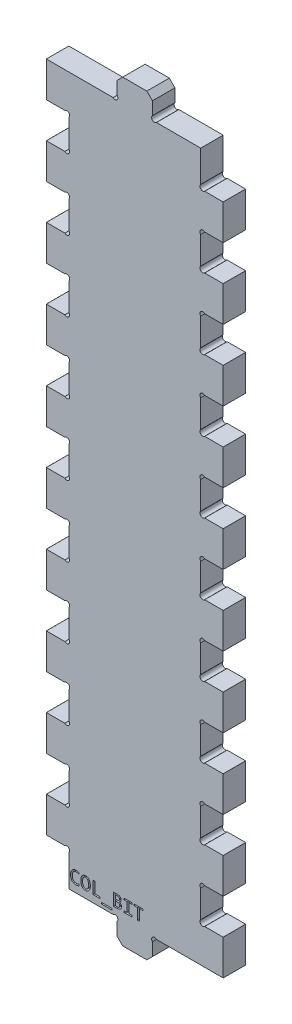
SolidWorks part; units mm, degrees
material "PVC Rigid"
ref_plane "Front Plane" through (0, 0, 0) normal (0, 0, 1) x (1, 0, 0)
ref_plane "Top Plane" through (0, 0, 0) normal (0, 1, 0) x (1, 0, 0)
ref_plane "Right Plane" through (0, 0, 0) normal (1, 0, 0) x (0, 0, -1)
sketch "Model" [suppressed]
  dimension "D3" = 0.7937
  dimension "D1" = 10
  dimension "D2" = 10
sketch "Sketch1" plane through (0, 0, 0) normal (0, 0, 1) x (1, 0, 0)
  line L1 (0, 0) -> (50, 0)
  line L2 (0, 0) -> (0, 200.0001)
  line L3 (0, 200.0001) -> (50, 200.0001)
  line L4 (50, 0) -> (50, 200.0001)
  dimension "D1" = 200.0001
  dimension "D2" = 50
extrude "Boss-Extrude1" add sketch "Sketch1" along normal blind 6.35
sketch "Sketch2" plane through (0, 0, 0) normal (0, 0, 1) x (1, 0, 0)
  line L0 (0, 100.0001) -> (50, 100.0001) construction
  line L1 (50, 200.0001) -> (0, 200.0001) construction
  line L2 (25, 200.0001) -> (25, 203.1751) construction
  line L3 (20, 206.3501) -> (30, 206.3501)
  line L4 (20, 206.3501) -> (20, 200.0001)
  line L5 (20, 200.0001) -> (30, 200.0001)
  line L6 (30, 206.3501) -> (30, 200.0001)
  line L7 (20, 206.3501) -> (30, 200.0001) construction
  line L8 (20, 200.0001) -> (30, 206.3501) construction
  line L9 (0, 200.0001) -> (0, 0) construction
  line L10 (50, 0) -> (50, 200.0001) construction
  line L11 (20, 0) -> (30, -6.35) construction
  line L12 (20, -6.35) -> (30, 0) construction
  line L13 (25, 0) -> (25, -3.175) construction
  line L14 (30, -6.35) -> (30, 0)
  line L15 (20, 0) -> (30, 0)
  line L16 (20, -6.35) -> (20, 0)
  line L17 (20, -6.35) -> (30, -6.35)
  dimension "D1" = 6.35
  dimension "D2" = 10
extrude "Boss-Extrude2" add sketch "Sketch2" along normal blind 6.35
sketch "Sketch3" plane through (0, 0, 6.35) normal (0, 0, 1) x (1, 0, 0)
  line L0 (25, 206.3501) -> (25, -6.35) construction
  line L1 (30, 206.3501) -> (20, 206.3501) construction
  line L2 (20, -6.35) -> (30, -6.35) construction
  line L3 (6.35, 200.0001) -> (6.35, 0) construction
  line L4 (20, 200.0001) -> (0, 200.0001) construction
  line L5 (0, 0) -> (20, 0) construction
  line L6 (0, 200.0001) -> (0, 0) construction
  line L7 (6.35, 0) -> (0, 0)
  line L8 (6.35, 0) -> (6.35, 10)
  line L9 (6.35, 10) -> (0, 10)
  line L10 (0, 0) -> (0, 10)
  line L11 (50, 0) -> (50, 10)
  line L12 (43.65, 10) -> (50, 10)
  line L13 (43.65, 0) -> (43.65, 10)
  line L14 (43.65, 0) -> (50, 0)
  dimension "D1" = 6.35
  dimension "D2" = 10
extrude "Cut-Extrude1" [suppressed] cut sketch "Sketch3" against normal blind 6.35
pattern_linear "LPattern2" [suppressed] count 10 spacing 20
sketch "Sketch4" [suppressed] plane through (0, 0, 6.35) normal (0, 0, 1) x (1, 0, 0)
  line L0 (0, 10) -> (6.35, 0) construction
  line L1 (6.35, 10) -> (5.2275, 10) construction
  line L2 (0.5613, 0.5613) -> (5.7887, 0.5613) construction
  line L3 (0.5613, 0.5613) -> (0.5613, 9.4387) construction
  line L4 (0.5613, 9.4387) -> (5.7887, 9.4387) construction
  line L5 (5.7887, 0.5613) -> (5.7887, 9.4387) construction
  line L6 (0.5613, 0.5613) -> (5.7887, 9.4387) construction
  line L7 (0.5613, 9.4387) -> (5.7887, 0.5613) construction
  line L8 (6.35, 10) -> (0, 10) construction
  line L9 (6.35, 10) -> (6.35, 8.8775) construction
  line L10 (6.35, 0) -> (6.35, 10) construction
  line L11 (25, 206.3501) -> (25, -6.35) construction
  line L12 (30, 206.3501) -> (20, 206.3501) construction
  line L13 (20, -6.35) -> (30, -6.35) construction
  line L14 (44.2113, 9.4387) -> (44.2113, 20.5613) construction
  line L15 (43.65, 10) -> (43.65, 8.8775) construction
  line L16 (49.4387, 9.4387) -> (44.2113, 0.5613) construction
  line L17 (49.4387, 0.5613) -> (44.2113, 9.4387) construction
  line L18 (44.2113, 0.5613) -> (44.2113, 9.4387) construction
  line L19 (49.4387, 9.4387) -> (44.2113, 9.4387) construction
  line L20 (49.4387, 0.5613) -> (49.4387, 9.4387) construction
  line L21 (49.4387, 0.5613) -> (44.2113, 0.5613) construction
  line L22 (43.65, 10) -> (44.7725, 10) construction
  line L23 (5.7887, 9.4387) -> (5.7887, 20.5613) construction
  line L24 (50, 10) -> (43.65, 0) construction
  circle A0 centre (5.7887, 9.4387) radius 0.7938
  circle A4 centre (5.7887, 20.5613) radius 0.7938
  circle A7 centre (44.2113, 20.5613) radius 0.7937
  circle A8 centre (44.2113, 9.4387) radius 0.7937
  point P4 (3.175, 5)
  point P40 (46.825, 5)
  dimension "D1" = 1.5875
extrude "Cut-Extrude3" [suppressed] cut sketch "Sketch4" against normal blind 6.35
pattern_linear "LPattern3" [suppressed] count 9 spacing 20
sketch "Sketch8" plane through (0, 0, 6.35) normal (0, 0, 1) x (1, 0, 0)
  line L0 (6.35, 200.0001) -> (6.35, 0) construction
  line L1 (20, 200.0001) -> (0, 200.0001) construction
  line L2 (0, 0) -> (20, 0) construction
  line L3 (0, 200.0001) -> (0, 0) construction
  line L4 (43.65, 200.0001) -> (43.65, 0) construction
  line L5 (0, 0) -> (6.35, 0)
  line L6 (0, 0) -> (0, 10)
  line L7 (0, 10) -> (6.35, 10)
  line L8 (6.35, 0) -> (6.35, 10)
  line L9 (50, 200.0001) -> (30, 200.0001) construction
  line L10 (30, 0) -> (50, 0) construction
  line L11 (50, 0) -> (50, 200.0001) construction
  line L12 (43.65, 10) -> (50, 10)
  line L13 (43.65, 10) -> (43.65, 20)
  line L14 (43.65, 20) -> (50, 20)
  line L15 (50, 10) -> (50, 20)
  dimension "D1" = 6.35
  dimension "D2" = 10
  dimension "D3" = 10
  dimension "D4" = 6.35
  dimension "D5" = 10
extrude "Cut-Extrude6" cut sketch "Sketch8" against normal through all
pattern_linear "LPattern4" count 10 spacing 20 along (0, 1, 0) of "Cut-Extrude6"
sketch "Sketch9" plane through (0, 0, 6.35) normal (0, 0, 1) x (1, 0, 0)
  line L0 (0, 30) -> (6.35, 20) construction
  line L1 (6.35, 30) -> (5.2275, 30) construction
  line L2 (0.5613, 20.5613) -> (5.7887, 20.5613) construction
  line L3 (0.5613, 20.5613) -> (0.5613, 29.4388) construction
  line L4 (0.5613, 29.4388) -> (5.7887, 29.4388) construction
  line L5 (5.7887, 20.5613) -> (5.7887, 29.4388) construction
  line L6 (0.5613, 20.5613) -> (5.7887, 29.4388) construction
  line L7 (0.5613, 29.4388) -> (5.7887, 20.5613) construction
  line L8 (6.35, 30) -> (0, 30) construction
  line L9 (6.35, 30) -> (6.35, 28.8775) construction
  line L10 (6.35, 20) -> (6.35, 30) construction
  line L11 (43.65, 20) -> (50, 10) construction
  line L12 (43.65, 20) -> (44.7725, 20) construction
  line L13 (44.2113, 10.5613) -> (49.4387, 10.5613) construction
  line L14 (44.2113, 10.5613) -> (44.2113, 19.4387) construction
  line L15 (44.2113, 19.4387) -> (49.4387, 19.4387) construction
  line L16 (49.4387, 10.5613) -> (49.4387, 19.4387) construction
  line L17 (44.2113, 10.5613) -> (49.4387, 19.4387) construction
  line L18 (44.2113, 19.4387) -> (49.4387, 10.5613) construction
  line L19 (50, 20) -> (43.65, 20) construction
  line L20 (43.65, 20) -> (43.65, 18.8775) construction
  line L21 (43.65, 20) -> (43.65, 10) construction
  line L22 (50, 20) -> (50, 30) construction
  circle A0 centre (5.7887, 29.4388) radius 0.7938
  circle A1 centre (5.7887, 20.5613) radius 0.7938
  circle A2 centre (44.2113, 19.4387) radius 0.7937
  circle A3 centre (44.2113, 10.5613) radius 0.7937
  point P4 (3.175, 25)
  point P23 (46.825, 15)
  dimension "D1" = 1.5875
  dimension "D2" = 10
extrude "Cut-Extrude7" cut sketch "Sketch9" against normal through all
pattern_linear "LPattern5" count 9 spacing 20 along (0, 1, 0) of "Cut-Extrude7"
sketch "Sketch10" plane through (0, 0, 6.35) normal (0, 0, 1) x (1, 0, 0)
  line L0 (0, 10) -> (6.35, 0) construction
  line L1 (5.2275, 10) -> (6.35, 10) construction
  line L2 (0.5613, 0.5613) -> (5.7887, 0.5613) construction
  line L3 (0.5613, 0.5613) -> (0.5613, 9.4387) construction
  line L4 (0.5613, 9.4387) -> (5.7887, 9.4387) construction
  line L5 (5.7887, 0.5613) -> (5.7887, 9.4387) construction
  line L6 (0.5613, 0.5613) -> (5.7887, 9.4387) construction
  line L7 (0.5613, 9.4387) -> (5.7887, 0.5613) construction
  line L8 (6.35, 10) -> (0, 10) construction
  line L9 (6.35, 10) -> (6.35, 8.8775) construction
  line L10 (6.35, 0) -> (6.35, 10) construction
  line L11 (6.35, 5) -> (3.175, 5) construction
  line L12 (0, 200.0001) -> (50, 0) construction
  line L13 (43.65, 200.0001) -> (50, 190.0001) construction
  line L14 (44.7725, 190.0001) -> (43.65, 190.0001) construction
  line L15 (44.2113, 190.5614) -> (49.4387, 190.5614) construction
  line L16 (44.2113, 190.5614) -> (44.2113, 199.4388) construction
  line L17 (44.2113, 199.4388) -> (49.4387, 199.4388) construction
  line L18 (49.4387, 190.5614) -> (49.4387, 199.4388) construction
  line L19 (44.2113, 190.5614) -> (49.4387, 199.4388) construction
  line L20 (44.2113, 199.4388) -> (49.4387, 190.5614) construction
  line L21 (43.65, 190.0001) -> (50, 190.0001) construction
  line L22 (43.65, 190.0001) -> (43.65, 191.1226) construction
  line L23 (43.65, 200.0001) -> (43.65, 190.0001) construction
  circle A0 centre (5.7887, 9.4387) radius 0.7938
  circle A2 centre (44.2113, 190.5614) radius 0.7937
  point P4 (3.175, 5)
  point P28 (46.825, 195.0001)
  dimension "D1" = 1.5875
  dimension "D2" = 1.5875
extrude "Cut-Extrude8" cut sketch "Sketch10" against normal through all
chamfer "Chamfer1" distance 1.5875 angle 45 4 edges at (30, -6.35, 3.175) (20, -6.35, 3.175) (20, 206.3501, 3.175) (30, 206.3501, 3.175)
sketch "Sketch5" [suppressed] plane through (0, 0, 6.35) normal (0, 0, 1) x (1, 0, 0)
  line L0 (6.35, 180.0001) -> (0, 190.0001) construction
  line L1 (6.35, 190.0001) -> (5.2275, 190.0001) construction
  line L2 (0.5613, 180.5614) -> (5.7887, 180.5614) construction
  line L3 (0.5613, 180.5614) -> (0.5613, 189.4388) construction
  line L4 (0.5613, 189.4388) -> (5.7887, 189.4388) construction
  line L5 (5.7887, 180.5614) -> (5.7887, 189.4388) construction
  line L6 (0.5613, 180.5614) -> (5.7887, 189.4388) construction
  line L7 (0.5613, 189.4388) -> (5.7887, 180.5614) construction
  line L8 (6.35, 190.0001) -> (0, 190.0001) construction
  line L9 (6.35, 190.0001) -> (6.35, 188.8776) construction
  line L10 (6.35, 181.1226) -> (6.35, 190.0001) construction
  line L15 (25, 206.3501) -> (25, -6.35) construction
  line L16 (28.4125, 206.3501) -> (21.5875, 206.3501) construction
  line L17 (21.5875, -6.35) -> (28.4125, -6.35) construction
  line L20 (43.65, 190.0001) -> (43.65, 188.8776) construction
  line L21 (49.4387, 189.4388) -> (44.2113, 180.5614) construction
  line L22 (49.4387, 180.5614) -> (44.2113, 189.4388) construction
  line L23 (44.2113, 180.5614) -> (44.2113, 189.4388) construction
  line L24 (49.4387, 189.4388) -> (44.2113, 189.4388) construction
  line L25 (49.4387, 180.5614) -> (49.4387, 189.4388) construction
  line L26 (49.4387, 180.5614) -> (44.2113, 180.5614) construction
  line L27 (43.65, 190.0001) -> (44.7725, 190.0001) construction
  line L28 (43.65, 180.0001) -> (50, 190.0001) construction
  line L29 (50, 100.0001) -> (0, 100.0001) construction
  arc A0 (5.2275, 180.0001) -> (6.35, 181.1226) centre (5.7887, 180.5614) ccw construction
  circle A1 centre (5.7887, 189.4388) radius 0.7938
  circle A4 centre (44.2113, 189.4388) radius 0.7937
  point P6 (3.175, 185.0001)
  point P51 (46.825, 185.0001)
  point P56 (25, 100.0001)
  dimension "D1" = 1.5875
extrude "Cut-Extrude4" [suppressed] cut sketch "Sketch5" against normal blind 6.35
sketch "Sketch11" plane through (0, 0, 0) normal (0, 0, 1) x (1, 0, 0)
  line L0 (28.4125, 206.3501) -> (21.5875, 206.3501) construction
  line L11 (20, 201.1226) -> (20, 200.0001) construction
  line L13 (20, 200.0001) -> (18.8775, 200.0001) construction
  line L15 (25, 206.3501) -> (25, -6.35) construction
  line L18 (30, 200.0001) -> (31.1225, 200.0001) construction
  line L19 (30, 201.1226) -> (30, 200.0001) construction
  line L29 (50, 100.0001) -> (0, 100.0001) construction
  circle A2 centre (19.4387, 200.5614) radius 0.7937
  circle A3 centre (30.5613, 200.5614) radius 0.7937
  circle A5 centre (19.4387, -0.5613) radius 0.7937
  circle A6 centre (30.5613, -0.5613) radius 0.7937
  point P56 (25, 100.0001)
  dimension "D1" = 1.5875
  dimension "D2" = 19.4387
  dimension "D3" = 100.0001
  dimension "D4" = 200.0001
extrude "Cut-Extrude10" cut sketch "Sketch11" along normal through all
sketch "Sketch6" [suppressed] plane through (0, 0, 6.35) normal (0, 0, 1) x (1, 0, 0)
  line L0 (6.604, 2.032) -> (43.65, 2.032) construction
  line L1 (43.65, 10) -> (43.65, 0) construction
  line L2 (6.35, 0) -> (18.8775, 0) construction
  line L4 (0, 20) -> (0, 10) construction
  text T0 "COL_BIT" font "Consolas" height 3.5
  dimension "D1" = 2.032
  dimension "D2" = 6.604
extrude "Cut-Extrude5" [suppressed] cut sketch "Sketch6" against normal blind 2.54
sketch "Sketch12" plane through (0, 0, 6.35) normal (0, 0, 1) x (1, 0, 0)
  line L0 (6.604, 2.032) -> (40.0372, 2.032) construction
  text T0 "COL_BIT" font "Consolas" height 3.5
  dimension "D1" = 2.032
  dimension "D2" = 6.604
extrude "Cut-Extrude11" cut sketch "Sketch12" against normal blind 2.54
sketch "Sketch13" [suppressed] plane through (0, 0, 6.35) normal (0, 0, 1) x (1, 0, 0)
  line L0 (0, 10) -> (6.35, 0) construction
  line L1 (5.2275, 10) -> (0, 10) construction
  line L2 (6.337, -0.0127) -> (0.013, -0.0127)
  line L3 (6.337, -0.0127) -> (6.337, 10.0127)
  line L4 (6.337, 10.0127) -> (0.013, 10.0127)
  line L5 (0.013, -0.0127) -> (0.013, 10.0127)
  line L6 (6.337, -0.0127) -> (0.013, 10.0127) construction
  line L7 (6.337, 10.0127) -> (0.013, -0.0127) construction
  line L8 (25, 206.3501) -> (25, -6.35) construction
  line L9 (28.4125, 206.3501) -> (21.5875, 206.3501) construction
  line L10 (21.5875, -6.35) -> (28.4125, -6.35) construction
  line L11 (43.663, 10.0127) -> (49.987, -0.0127) construction
  line L12 (43.663, -0.0127) -> (49.987, 10.0127) construction
  line L13 (50, 10) -> (43.65, 0) construction
  line L14 (49.987, -0.0127) -> (49.987, 10.0127)
  line L15 (43.663, 10.0127) -> (49.987, 10.0127)
  line L16 (43.663, -0.0127) -> (43.663, 10.0127)
  line L17 (43.663, -0.0127) -> (49.987, -0.0127)
  arc A0 (6.35, 8.8775) -> (5.2275, 10) centre (5.7887, 9.4387) ccw construction
  point P4 (3.175, 5)
  point P26 (46.825, 5)
  dimension "D1" = 0.0127
extrude "Cut-Extrude12" [suppressed] cut sketch "Sketch13" against normal through all
pattern_linear "LPattern6" [suppressed] count 10 spacing 20
sketch "Sketch14" plane through (0, 0, 6.35) normal (0, 0, 1) x (1, 0, 0)
  line L0 (0, 10) -> (6.35, 0) construction
  line L1 (5.2275, 10) -> (0, 10) construction
  line L2 (0.013, -0.0127) -> (6.337, -0.0127)
  line L3 (0.013, -0.0127) -> (0.013, 10.0127)
  line L4 (0.013, 10.0127) -> (6.337, 10.0127)
  line L5 (6.337, -0.0127) -> (6.337, 10.0127)
  line L6 (0.013, -0.0127) -> (6.337, 10.0127) construction
  line L7 (0.013, 10.0127) -> (6.337, -0.0127) construction
  line L8 (43.65, 20) -> (50, 10) construction
  line L9 (50, 20) -> (44.7725, 20) construction
  line L10 (43.663, 9.9873) -> (49.987, 9.9873)
  line L11 (43.663, 9.9873) -> (43.663, 20.0127)
  line L12 (43.663, 20.0127) -> (49.987, 20.0127)
  line L13 (49.987, 9.9873) -> (49.987, 20.0127)
  line L14 (43.663, 9.9873) -> (49.987, 20.0127) construction
  line L15 (43.663, 20.0127) -> (49.987, 9.9873) construction
  arc A0 (6.35, 8.8775) -> (5.2275, 10) centre (5.7887, 9.4387) ccw construction
  arc A1 (44.7725, 20) -> (43.65, 18.8775) centre (44.2113, 19.4387) ccw construction
  point P4 (3.175, 5)
  point P9 (46.825, 15)
  point P27 (0, 0)
  dimension "D1" = 0.0127
  dimension "D2" = 0.0127
extrude "Cut-Extrude13" cut sketch "Sketch14" against normal through all
pattern_linear "LPattern7" count 10 spacing 20 along (0, 1, 0) of "Cut-Extrude13"
equation "\"tHeight\"=0.25"
equation "\"D1@Sketch2\"=\"tHeight\""
equation "\"tWidth\"=0.393701"
equation "\"D2@Sketch2\"=\"tWidth\""
equation "\"D1@Sketch1\"=\"tWidth\"*20"
equation "\"D1@Sketch3\"=\"tHeight\""
equation "\"D2@Sketch3\"=\"tWidth\""
equation "\"D3@LPattern1\"=\"tWidth\"*2"
equation "\"D3@LPattern2\"=\"tWidth\"*2"
equation "\"D3@LPattern3\"=\"tWidth\"*2"
equation "\"D1@Sketch8\"=\"tHeight\""
equation "\"D2@Sketch8\"=\"tWidth\""
equation "\"D3@Sketch8\"=\"tWidth\""
equation "\"D4@Sketch8\"=\"tHeight\""
equation "\"D5@Sketch8\"=\"tWidth\""
equation "\"D3@LPattern4\"=\"tWidth\"*2"
equation "\"D3@LPattern5\"=\"tWidth\"*2"
equation "\"D2@Sketch9\"=\"tWidth\""
equation "\"tol\"=0.0005"
equation "\"D1@Sketch13\"=\"tol\""
equation "\"D3@LPattern6\"=\"tWidth\"*2"
equation "\"D1@Sketch14\"=\"tol\""
equation "\"D2@Sketch14\"=\"tol\""
